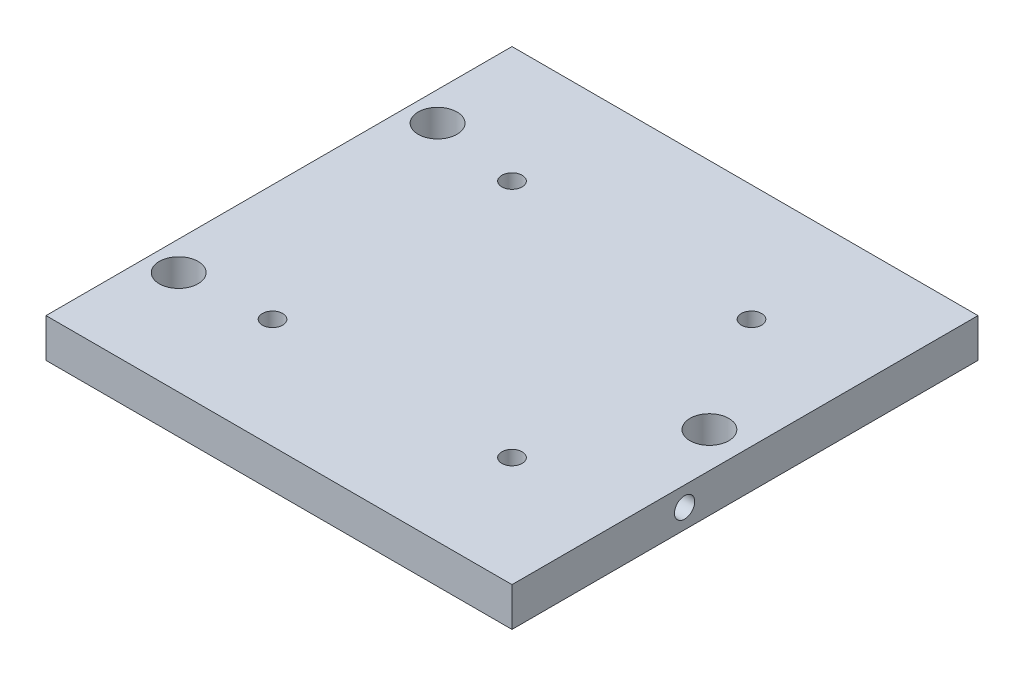
SolidWorks part; units mm, degrees
ref_plane "Front Plane" through (0, 0, 0) normal (0, 0, 1) x (1, 0, 0)
ref_plane "Top Plane" through (0, 0, 0) normal (0, 1, 0) x (1, 0, 0)
ref_plane "Right Plane" through (0, 0, 0) normal (1, 0, 0) x (0, 0, -1)
sketch "Sketch1" plane through (0, 0, 0) normal (0, 1, 0) x (1, 0, 0)
  line L1 (-32.9406, 33.1391) -> (81.3594, 33.1391)
  line L2 (-32.9406, 33.1391) -> (-32.9406, -81.1609)
  line L3 (-32.9406, -81.1609) -> (81.3594, -81.1609)
  line L4 (81.3594, 33.1391) -> (81.3594, -81.1609)
  dimension "D1" = 114.3
  dimension "D2" = 114.3
extrude "Seebeck Middle Block" add sketch "Sketch1" along normal blind 9.525
sketch "Sketch2" plane through (-32.9406, 0, 0) normal (-1, 0, 0) x (0, 0, 1)
  line L0 (-33.1391, 9.525) -> (-33.1391, 0) construction
  line L1 (-33.1391, 0) -> (81.1609, 0) construction
  circle A0 centre (24.0109, 3.175) radius 0.7937
  point P4 (24.0109, 0)
  dimension "D1" = 1.5875
  dimension "D2" = 57.15
  dimension "D3" = 3.175
extrude "Thermo Couple Hole" cut sketch "Sketch2" against normal blind 60.325
sketch "Sketch3" plane through (0, 9.525, 0) normal (0, 1, 0) x (1, 0, 0)
  line L0 (-32.9406, -81.1609) -> (81.3594, -81.1609) construction
  line L1 (-32.9406, 33.1391) -> (-32.9406, -81.1609) construction
  line L3 (81.3594, 33.1391) -> (-32.9406, 33.1391) construction
  circle A0 centre (-25.7969, -55.7609) radius 4.7625
  circle A1 centre (-25.7969, 7.7391) radius 4.7625
  circle A2 centre (72.6281, -24.0109) radius 4.7625
  dimension "D1" = 9.525
  dimension "D2" = 9.525
  dimension "D3" = 9.525
  dimension "D4" = 25.4
  dimension "D5" = 7.1437
  dimension "D6" = 7.1437
  dimension "D7" = 25.4
  dimension "D8" = 57.15
  dimension "D9" = 26.9875
extrude "Middle Mounting holes" cut sketch "Sketch3" against normal through all
hole_wizard "#9 (0.196) TEG Mount Hole" positions "Sketch6" profile "Sketch5" hole size "#9" standard "ANSI Inch"
sketch "Sketch6" plane through (0, 9.525, 0) normal (0, 1, 0) x (1, 0, 0)
  line L0 (-32.9406, 33.1391) -> (-32.9406, -81.1609) construction
  line L1 (81.3594, 33.1391) -> (-32.9406, 33.1391) construction
  line L2 (81.3594, -81.1609) -> (81.3594, 33.1391) construction
  line L3 (-32.9406, -81.1609) -> (81.3594, -81.1609) construction
  point P0 (-4.3656, 4.5641)
  point P2 (54.3719, 4.5641)
  point P4 (54.3719, -54.1734)
  point P6 (-4.3656, -54.1734)
  dimension "D1" = 28.575
  dimension "D2" = 28.575
  dimension "D3" = 26.9875
  dimension "D4" = 28.575
  dimension "D5" = 26.9875
  dimension "D6" = 26.9875
  dimension "D7" = 28.575
  dimension "D8" = 26.9875
sketch "Sketch5" plane through (-4.3656, 9.525, -4.5641) normal (1, 0, 0) x (0, 0, 1)
  line L0 (0, 0) -> (0, 7.8457)
  line L1 (0, 7.8457) -> (2.4892, 6.35)
  line L2 (2.4892, 6.35) -> (2.4892, 0)
  line L5 (2.4892, 0) -> (0, 0)
  line L10 (0, 7.8457) -> (-2.4892, 6.35) construction
  line L11 (0, -6.35) -> (0, 107.95) construction
  dimension "Hole Dia." = 4.9784
  dimension "Hole Depth" = 6.35
  dimension "Drill Angle" = 118
hole_wizard "#9 (0.196) Voltage Hole" positions "Sketch8" profile "Sketch7" hole size "#9" standard "ANSI Inch"
sketch "Sketch8" plane through (81.3594, 0, 0) normal (1, 0, 0) x (0, 0, -1)
  line L0 (-81.1609, 0) -> (33.1391, 0) construction
  line L1 (-81.1609, 9.525) -> (-81.1609, 0) construction
  point P0 (-38.8276, 4.7625)
  dimension "D1" = 4.7625
  dimension "D2" = 42.3333
sketch "Sketch7" plane through (81.3594, 4.7625, 38.8276) normal (0, 1, 0) x (0, 0, -1)
  line L0 (0, 0) -> (0, 14.1957)
  line L1 (0, 14.1957) -> (2.4892, 12.7)
  line L2 (2.4892, 12.7) -> (2.4892, 0)
  line L5 (2.4892, 0) -> (0, 0)
  line L10 (0, 14.1957) -> (-2.4892, 12.7) construction
  line L11 (0, -6.35) -> (0, 107.95) construction
  dimension "Hole Dia." = 4.9784
  dimension "Hole Depth" = 12.7
  dimension "Drill Angle" = 118
